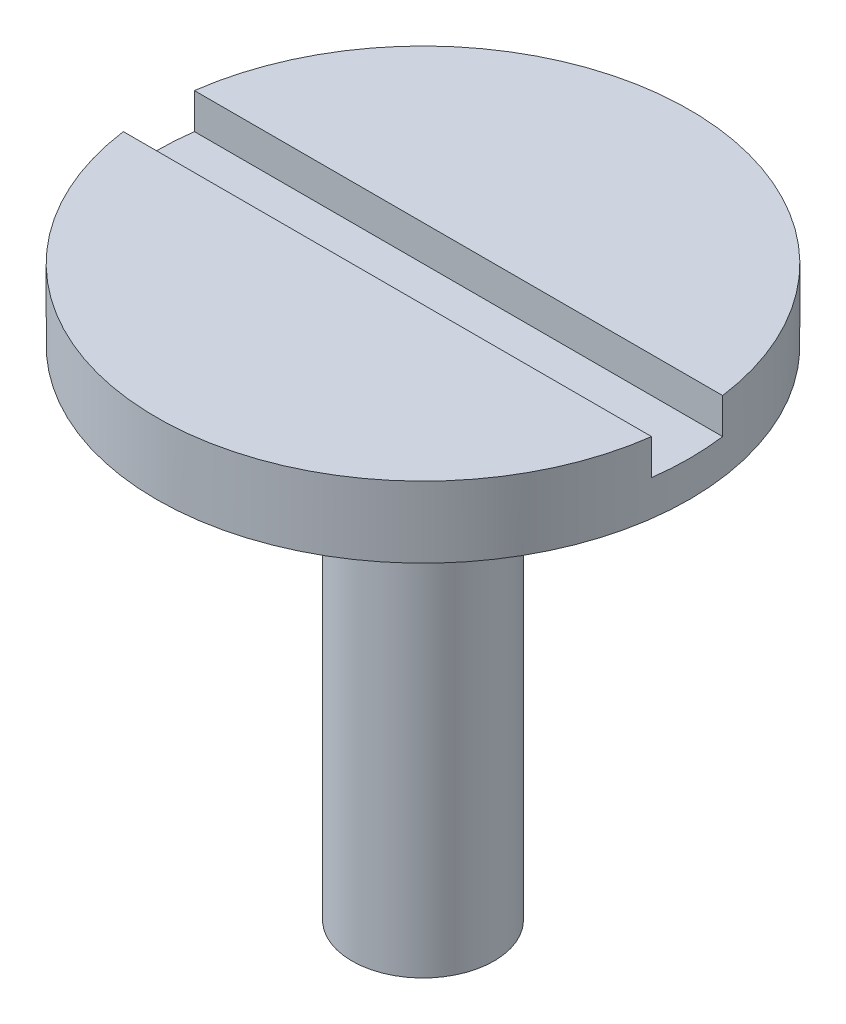
SolidWorks part; units mm, degrees
ref_plane "前视基准面" through (0, 0, 0) normal (0, 0, 1) x (1, 0, 0)
ref_plane "上视基准面" through (0, 0, 0) normal (0, 1, 0) x (1, 0, 0)
ref_plane "右视基准面" through (0, 0, 0) normal (1, 0, 0) x (0, 0, -1)
sketch "草图1" plane through (0, 0, 0) normal (0, 1, 0) x (1, 0, 0)
  circle A0 centre (0, 0) radius 1
  dimension "D1" = 2
extrude "拉伸1" add sketch "草图1" along normal blind 7
sketch "草图2" plane through (0, 7, 0) normal (0, 1, 0) x (-1, 0, 0)
  circle A0 centre (0, 0) radius 3.75
  dimension "D1" = 7.5
extrude "拉伸2" add sketch "草图2" along normal blind 1
sketch "草图3" plane through (0, 8, 0) normal (0, 1, 0) x (-1, 0, 0)
  line L0 (4.0624, 0) -> (-4.2778, 0) construction
  line L1 (0, -3.5166) -> (0, 3.738) construction
  line L3 (4.1894, -0.5) -> (-4.1894, -0.5)
  line L4 (4.1894, -0.5) -> (4.1894, 0.5)
  line L5 (4.1894, 0.5) -> (-4.1894, 0.5)
  line L6 (-4.1894, -0.5) -> (-4.1894, 0.5)
  dimension "D1" = 1
extrude "切除-拉伸1" cut sketch "草图3" against normal blind 0.5
sketch "草图4" plane through (0, 8, 0) normal (0, 1, 0) x (-1, 0, 0)
  line L0 (0, -3.8639) -> (0, 3.6765) construction
  line L1 (1.7727, 0) -> (-1.7019, 0) construction
  line L2 (0.5, -5.623) -> (-0.5, -5.623)
  line L3 (0.5, -5.623) -> (0.5, 5.623)
  line L4 (0.5, 5.623) -> (-0.5, 5.623)
  line L5 (-0.5, -5.623) -> (-0.5, 5.623)
  dimension "D1" = 1
extrude "切除-拉伸2" [suppressed] cut sketch "草图4" against normal blind 0.5
